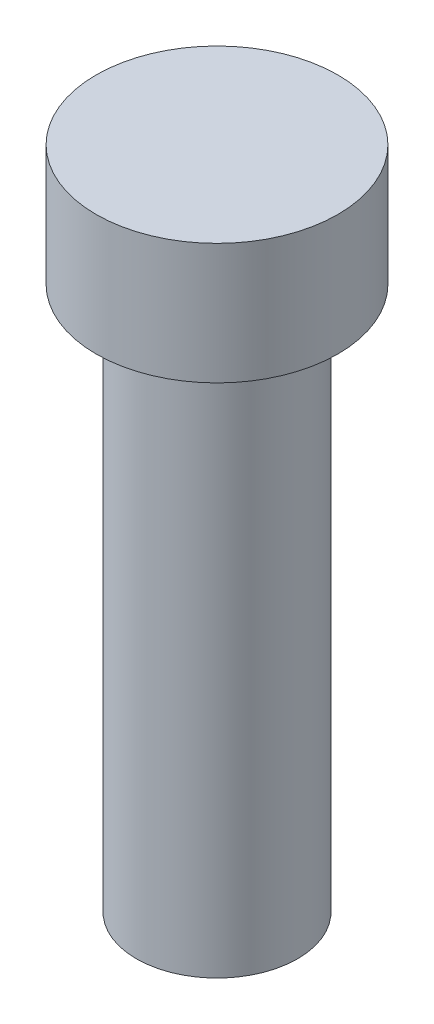
SolidWorks part; units mm, degrees
ref_plane "Front Plane" through (0, 0, 0) normal (0, 0, 1) x (1, 0, 0)
ref_plane "Top Plane" through (0, 0, 0) normal (0, 1, 0) x (1, 0, 0)
ref_plane "Right Plane" through (0, 0, 0) normal (1, 0, 0) x (0, 0, -1)
sketch "Sketch1" plane through (0, 0, 0) normal (0, 1, 0) x (1, 0, 0)
  circle A0 centre (0, 0) radius 3
  dimension "D1" = 6
extrude "Boss-Extrude1" add sketch "Sketch1" along normal blind 3
sketch "Sketch2" plane through (0, 0, 0) normal (0, -1, 0) x (1, 0, 0)
  circle A0 centre (0, 0) radius 2
  dimension "D1" = 4
extrude "Boss-Extrude2" add sketch "Sketch2" along normal blind 13.5
